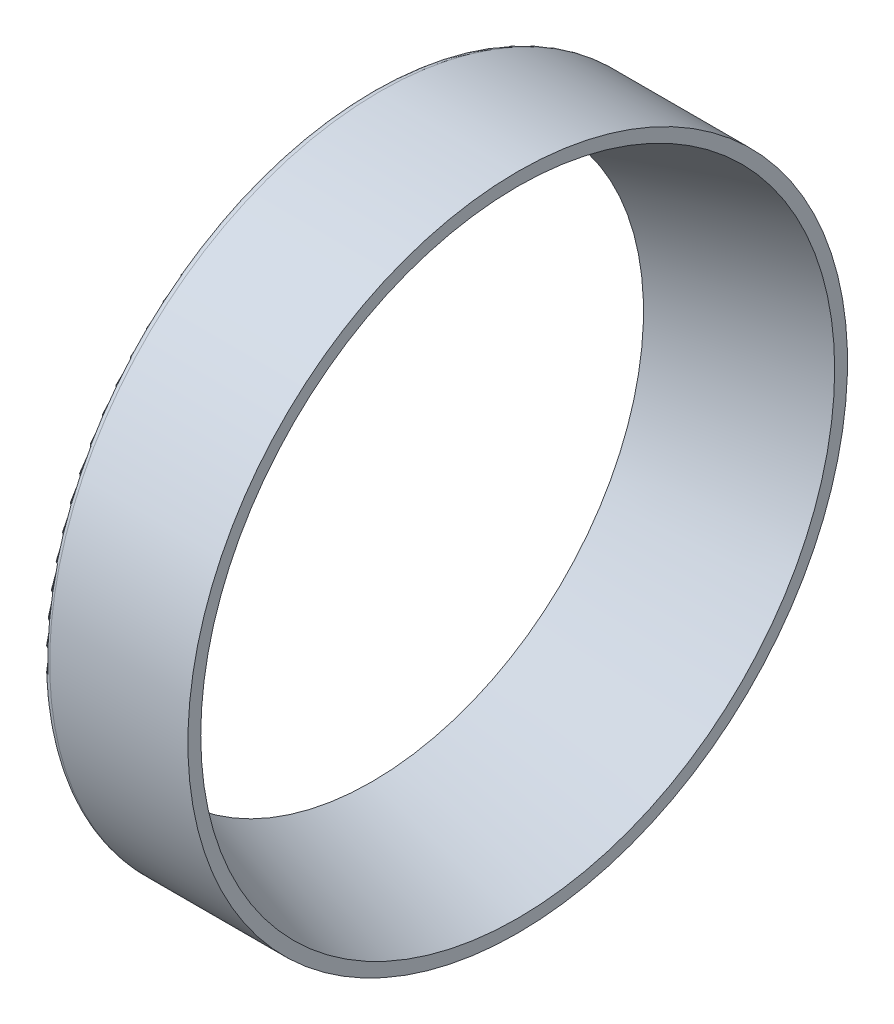
SolidWorks part; units mm, degrees
ref_plane "Plan1" through (0, 0, 0) normal (0, 0, 1) x (1, 0, 0)
ref_plane "Plan2" through (0, 0, 0) normal (0, 1, 0) x (1, 0, 0)
ref_plane "Plan3" through (0, 0, 0) normal (1, 0, 0) x (0, 0, -1)
sketch "Esquisse1" plane through (0, 0, 0) normal (0, 0, 1) x (1, 0, 0)
  line L0 (-16.6971, 22.9) -> (-16.6971, 18.9173)
  line L1 (-16.0971, 23.5) -> (-5.1971, 23.5)
  line L3 (-5.1971, 23.5) -> (-5.1971, 22.4879)
  line L4 (-5.1971, 22.4879) -> (-16.6971, 18.9173)
  line L5 (0, -2.5) -> (-37.0588, -2.5) construction
  arc A0 (-16.6971, 22.9) -> (-16.0971, 23.5) centre (-16.0971, 22.9) cw
  point P9 (-16.6971, 23.5)
  dimension "D5" = 0.6
  dimension "D1" = 26
  dimension "D2" = 11.5
  dimension "D3" = 17.249
  dimension "D4" = 1.0121
revolve "Base-Révolution" add sketch "Esquisse1" angle 360 about L5
